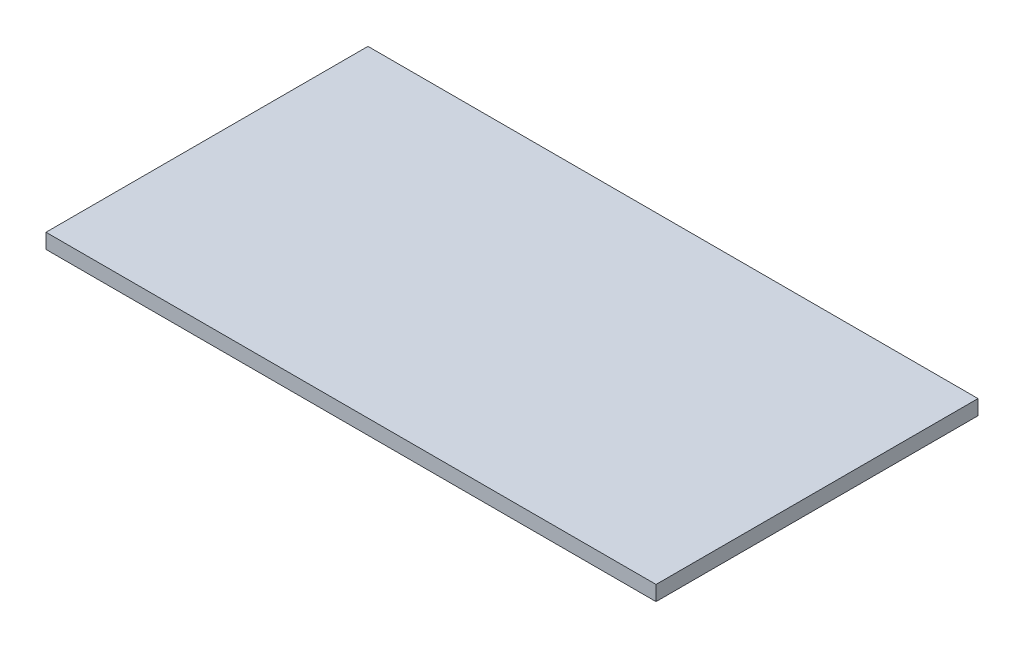
SolidWorks part; units mm, degrees
ref_plane "Front Plane" through (0, 0, 0) normal (0, 0, 1) x (1, 0, 0)
ref_plane "Top Plane" through (0, 0, 0) normal (0, 1, 0) x (1, 0, 0)
ref_plane "Right Plane" through (0, 0, 0) normal (1, 0, 0) x (0, 0, -1)
sketch "Sketch1" plane through (0, 0, 0) normal (0, 1, 0) x (1, 0, 0)
  line L1 (-114.3, -60.325) -> (114.3, -60.325)
  line L2 (-114.3, -60.325) -> (-114.3, 60.325)
  line L3 (-114.3, 60.325) -> (114.3, 60.325)
  line L4 (114.3, -60.325) -> (114.3, 60.325)
  line L5 (-114.3, -60.325) -> (114.3, 60.325) construction
  line L6 (-114.3, 60.325) -> (114.3, -60.325) construction
  point P0 (0, 0)
  dimension "D1" = 120.65
  dimension "D2" = 228.6
extrude "Boss-Extrude1" add sketch "Sketch1" along normal blind 5.588
